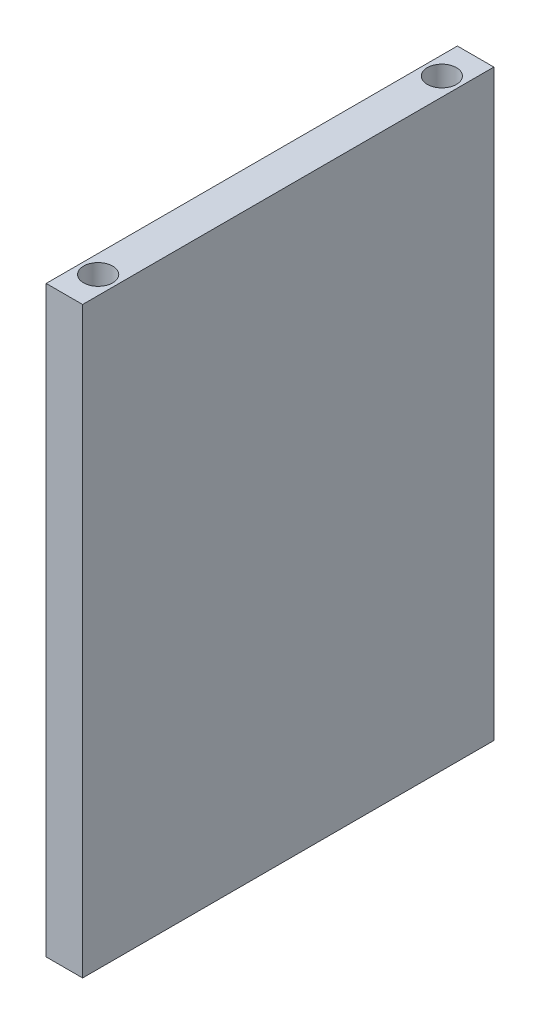
SolidWorks part; units mm, degrees
material "1060-H18"
ref_plane "Płaszczyzna przednia" through (0, 0, 0) normal (0, 0, 1) x (1, 0, 0)
ref_plane "Płaszczyzna górna" through (0, 0, 0) normal (0, 1, 0) x (1, 0, 0)
ref_plane "Płaszczyzna prawa" through (0, 0, 0) normal (1, 0, 0) x (0, 0, -1)
sketch "Szkic1" plane through (0, 0, 0) normal (1, 0, 0) x (0, 0, -1)
  line L1 (0, 0) -> (56.4, 0)
  line L2 (0, 0) -> (0, 80)
  line L3 (0, 80) -> (56.4, 80)
  line L4 (56.4, 0) -> (56.4, 80)
  dimension "D1" = 56.4
  dimension "D2" = 80
extrude "Dodanie-wyciągnięcie1" add sketch "Szkic1" along normal blind 5
sketch "Szkic2" plane through (0, 80, 0) normal (0, 1, 0) x (1, 0, 0)
  line L0 (2.5, 56.4) -> (2.5, 0) construction
  line L1 (5, 56.4) -> (0, 56.4) construction
  line L2 (5, 0) -> (0, 0) construction
  line L3 (0, 28.2) -> (5, 28.2) construction
  line L4 (0, 56.4) -> (0, 0) construction
  line L5 (5, 56.4) -> (5, 0) construction
  point P12 (2.5, 51.77)
  point P13 (2.5, 4.63)
  dimension "D1" = 47.14
hole_wizard "Otwory ustalające Ø4.0mm1" positions "Szkic 3D1" profile "Szkic3" hole size "Ø4.0" standard "ISO" end condition through all
sketch3d "Szkic 3D1"
  point P0 (2.5, 80, -51.77)
  point P3 (2.5, 80, -4.63)
sketch "Szkic3" plane through (2.5, 80, -51.77) normal (1, 0, 0) x (0, 0, 1)
  line L0 (0, 0) -> (0, 80)
  line L1 (0, 80) -> (2, 80)
  line L2 (2, 80) -> (2, 0)
  line L5 (2, 0) -> (0, 0)
  line L11 (0, -6.35) -> (0, 107.95) construction
  dimension "Średnica otworu na wylot" = 4
  dimension "Głębokość otworu na wylot" = 80
